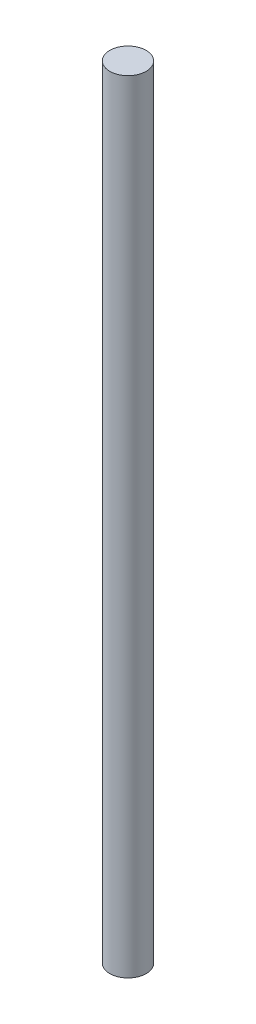
SolidWorks part; units mm, degrees
material "1060 合金"
ref_plane "前视基准面" through (0, 0, 0) normal (0, 0, 1) x (1, 0, 0)
ref_plane "上视基准面" through (0, 0, 0) normal (0, 1, 0) x (1, 0, 0)
ref_plane "右视基准面" through (0, 0, 0) normal (1, 0, 0) x (0, 0, -1)
other "Configuration Table"
sketch "草图1" plane through (0, 0, 0) normal (0, 1, 0) x (1, 0, 0)
  circle A0 centre (0, 0) radius 1
  dimension "D1" = 2
extrude "凸台-拉伸1" add sketch "草图1" along normal blind 43
